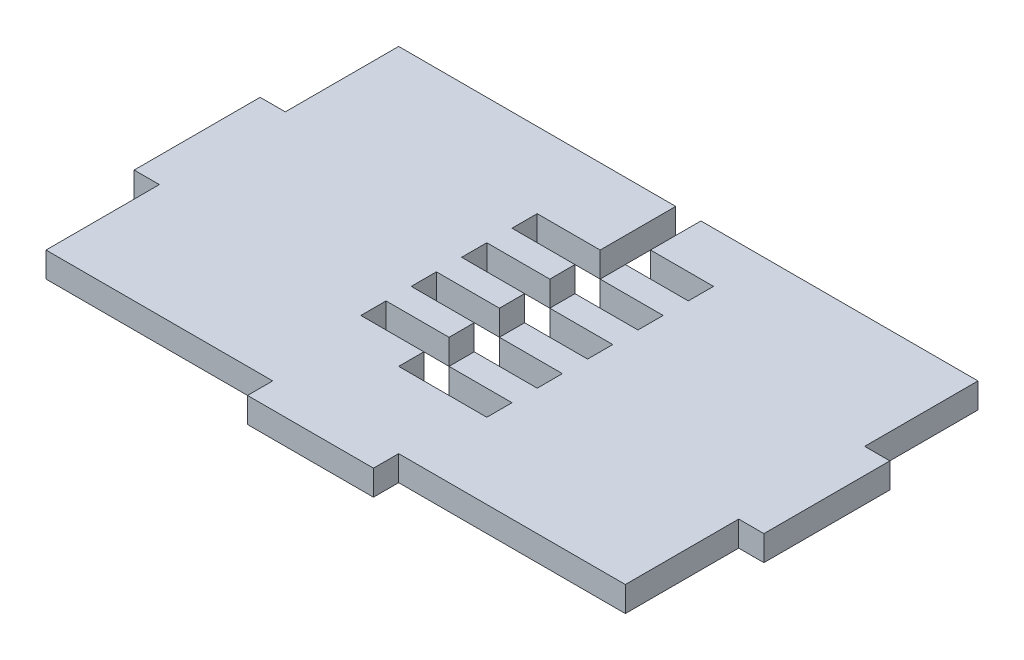
SolidWorks part; units mm, degrees
ref_plane "前视基准面" through (0, 0, 0) normal (0, 0, 1) x (1, 0, 0)
ref_plane "上视基准面" through (0, 0, 0) normal (0, 1, 0) x (1, 0, 0)
ref_plane "右视基准面" through (0, 0, 0) normal (1, 0, 0) x (0, 0, -1)
sketch "草图1" plane through (0, 0, 0) normal (0, 1, 0) x (1, 0, 0)
  line L1 (0, 0) -> (92, 0)
  line L2 (0, 0) -> (0, 56)
  line L3 (0, 56) -> (92, 56)
  line L4 (92, 0) -> (92, 56)
  line L5 (0, 38) -> (-4, 38)
  line L6 (0, 38) -> (0, 18)
  line L7 (0, 18) -> (-4, 18)
  line L8 (-4, 38) -> (-4, 18)
  line L9 (92, 38) -> (96, 38)
  line L10 (92, 38) -> (92, 18)
  line L11 (92, 18) -> (96, 18)
  line L12 (96, 38) -> (96, 18)
  line L13 (44, 56) -> (48, 56)
  line L14 (44, 56) -> (44, 12)
  line L15 (44, 12) -> (48, 12)
  line L16 (48, 56) -> (48, 12)
  line L22 (48, 34) -> (48, 36)
  line L34 (44, 44) -> (44, 40)
  line L42 (44, 28) -> (44, 24)
  line L45 (56, 0) -> (36, 0)
  line L46 (56, 0) -> (56, -4)
  line L47 (56, -4) -> (36, -4)
  line L48 (36, 0) -> (36, -4)
  line L50 (48, 24) -> (48, 12)
  line L53 (48, 16) -> (58, 16)
  line L54 (48, 16) -> (48, 12)
  line L55 (48, 12) -> (58, 12)
  line L56 (58, 16) -> (58, 12)
  line L57 (48, 20) -> (58, 20)
  line L58 (48, 20) -> (48, 24)
  line L59 (48, 24) -> (58, 24)
  line L60 (58, 20) -> (58, 24)
  line L61 (48, 32) -> (58, 32)
  line L62 (48, 32) -> (48, 28)
  line L63 (48, 28) -> (58, 28)
  line L64 (58, 32) -> (58, 28)
  line L65 (48, 40) -> (58, 40)
  line L66 (48, 40) -> (48, 36)
  line L67 (48, 36) -> (58, 36)
  line L68 (58, 40) -> (58, 36)
  line L69 (48, 48) -> (58, 48)
  line L70 (48, 48) -> (48, 44)
  line L71 (48, 44) -> (58, 44)
  line L72 (58, 48) -> (58, 44)
  line L73 (44, 44) -> (34, 44)
  line L74 (44, 44) -> (44, 40)
  line L75 (44, 40) -> (34, 40)
  line L76 (34, 44) -> (34, 40)
  line L77 (44, 36) -> (34, 36)
  line L78 (44, 36) -> (44, 32)
  line L79 (44, 32) -> (34, 32)
  line L80 (34, 36) -> (34, 32)
  line L81 (44, 28) -> (34, 28)
  line L82 (44, 28) -> (44, 24)
  line L83 (44, 24) -> (34, 24)
  line L84 (34, 28) -> (34, 24)
  line L85 (44, 20) -> (34, 20)
  line L86 (44, 20) -> (44, 16)
  line L87 (44, 16) -> (34, 16)
  line L88 (34, 20) -> (34, 16)
  point P5 (92, 28)
  point P6 (0, 28)
  point P7 (92, 38)
  point P8 (92, 20)
  point P9 (0, 38)
  point P10 (0, 20)
  point P19 (46, 56)
  point P20 (44, 56)
  point P21 (44, 56)
  point P26 (44, 44)
  point P27 (44, 48)
  point P28 (44, 36)
  point P29 (44, 40)
  point P30 (44, 32)
  point P31 (44, 28)
  point P32 (44, 24)
  point P33 (44, 12)
  point P34 (48, 24)
  point P35 (48, 28)
  point P36 (48, 32)
  point P37 (48, 36)
  point P38 (48, 44)
  point P39 (48, 48)
  point P41 (44, 20)
  point P42 (44, 16)
  point P43 (44, 12)
  point P44 (48, 16)
  point P46 (48, 20)
  point P55 (48, 40)
  point P68 (56, 0)
  point P69 (40, 0)
  point P70 (46, 0)
extrude "凸台-拉伸2" add sketch "草图1" along normal blind 4 contours L88 L85 L14 L83 L84 L81 L79 L80 L77 L75 L76 L73 L3 L2 L1 L4 L16 L69 L72 L71 L65 L68 L67 L61 L64 L63 L59 L60 L57 L50 L53 L56 L55 L15 L87 | L5 L8 L7 L2 | L1 L48 L47 L46 | L12 L9 L4 L11
